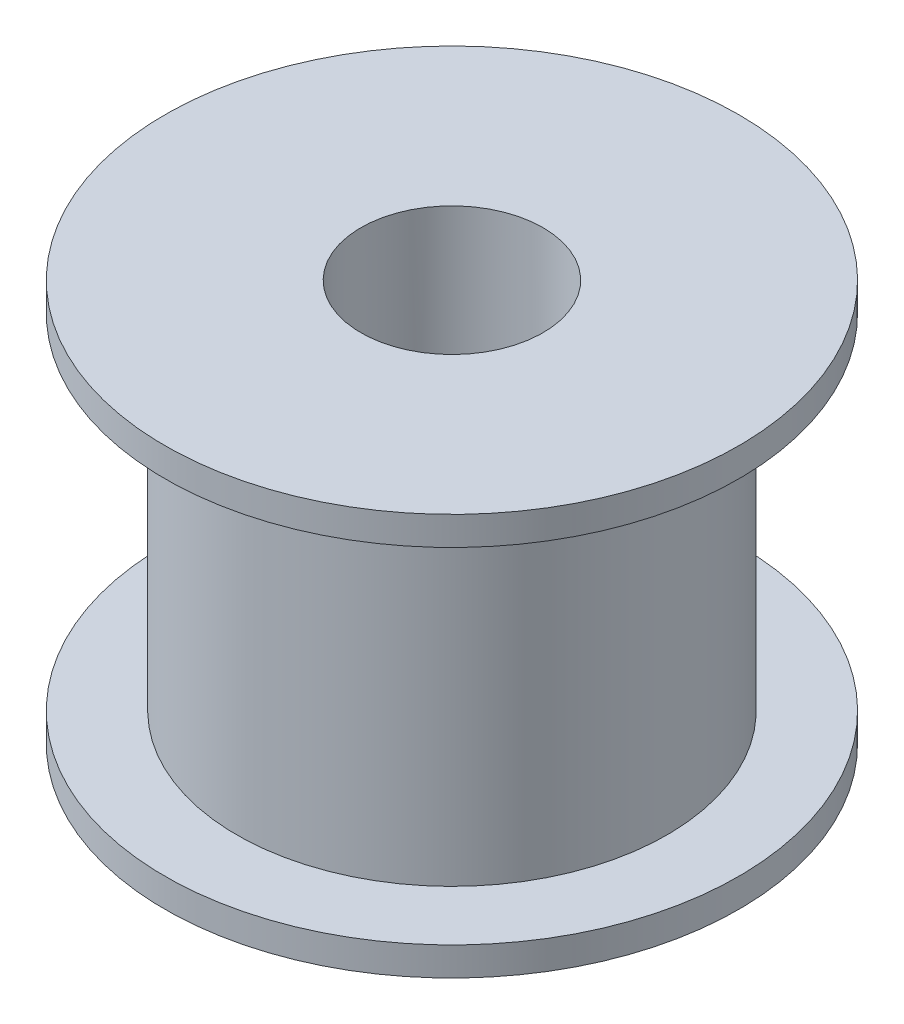
SolidWorks part; units mm, degrees
ref_plane "Front Plane" through (0, 0, 0) normal (0, 0, 1) x (1, 0, 0)
ref_plane "Top Plane" through (0, 0, 0) normal (0, 1, 0) x (1, 0, 0)
ref_plane "Right Plane" through (0, 0, 0) normal (1, 0, 0) x (0, 0, -1)
sketch "Sketch1" plane through (0, 0, 0) normal (0, 0, 1) x (1, 0, 0)
  line L0 (-3.175, 10) -> (-3.175, 24)
  line L1 (-3.175, 24) -> (-10, 24)
  line L2 (-10, 24) -> (-10, 23)
  line L3 (-10, 23) -> (-7.5, 23)
  line L4 (-7.5, 23) -> (-7.5, 11)
  line L5 (-7.5, 11) -> (-10, 11)
  line L6 (-10, 11) -> (-10, 10)
  line L7 (-10, 10) -> (-3.175, 10)
  line L10 (0, 0) -> (0, 23.1903) construction
  line L11 (0, 0) -> (-4.875, 0) construction
  dimension "D1" = 10
  dimension "D2" = 6.35
  dimension "D3" = 15
  dimension "D5" = 20
  dimension "D6" = 1
  dimension "D7" = 1
  dimension "D8" = 14
revolve "Revolve1" add sketch "Sketch1" angle 360 about L10
sketch "Sketch2" plane through (0, 0, 0) normal (0, 0, 1) x (1, 0, 0)
  line L0 (10, 24) -> (-10, 24) construction
  circle A0 centre (0, 17) radius 1.6
  dimension "D2" = 3.2
  dimension "D1" = 7
extrude "Cut-Extrude1" cut sketch "Sketch2" against normal up to next
sketch "Sketch3" plane through (0, 0, 0) normal (1, 0, 0) x (0, 0, -1)
  line L0 (10, 24) -> (-10, 24) construction
  circle A0 centre (0, 17) radius 1.6
  dimension "D1" = 7
  dimension "D2" = 3.2
extrude "Cut-Extrude2" cut sketch "Sketch3" against normal up to next
